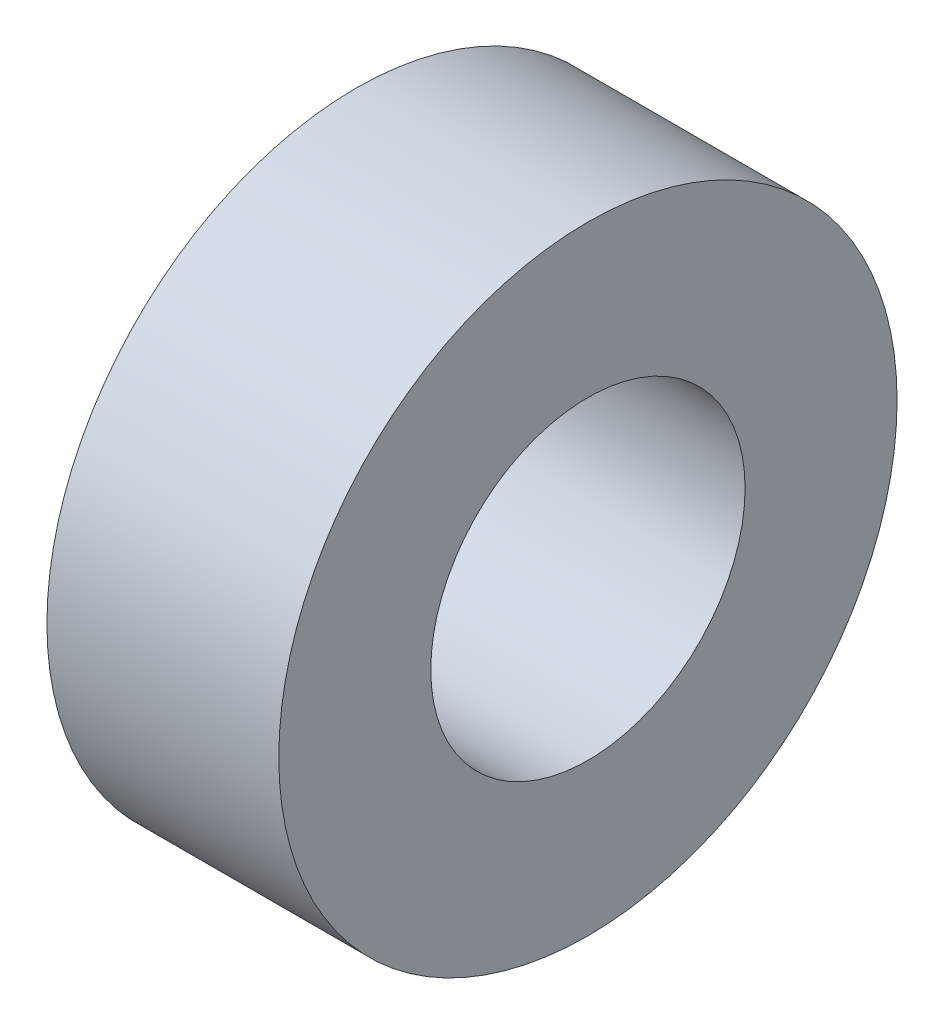
SolidWorks part; units mm, degrees
other "Preload Thrust Bearing F6 12M"
ref_plane "Front Plane" through (0, 0, 0) normal (0, 0, 1) x (1, 0, 0)
ref_plane "Top Plane" through (0, 0, 0) normal (0, 1, 0) x (1, 0, 0)
ref_plane "Right Plane" through (0, 0, 0) normal (1, 0, 0) x (0, 0, -1)
sketch3d "Part ring outside sketch datum points"
  point P0 (15, -29, -19.5)
  point P1 (15, -19, -19.5)
  point P2 (15, -29, -9.5)
ref_plane "Part ring outside sketch plane" through (15, 0, 0) normal (1, 0, 0) x (0, 0, -1)
sketch "Part ring outside sketch" plane through (15, 0, 0) normal (1, 0, 0) x (0, 0, -1)
  circle A0 centre (19.5, -29) radius 6
extrude "Part ring outside" add sketch "Part ring outside sketch" along normal blind 4.5 separate body
sketch3d "Part ring bore sketch datum points"
  point P0 (14.9, -29, -19.5)
  point P1 (14.9, -19, -19.5)
  point P2 (14.9, -29, -9.5)
ref_plane "Part ring bore sketch plane" through (14.9, 0, 0) normal (1, 0, 0) x (0, 0, -1)
sketch "Part ring bore sketch" plane through (14.9, 0, 0) normal (1, 0, 0) x (0, 0, -1)
  circle A0 centre (19.5, -29) radius 3.05
extrude "Part ring bore" cut sketch "Part ring bore sketch" along normal blind 4.7
